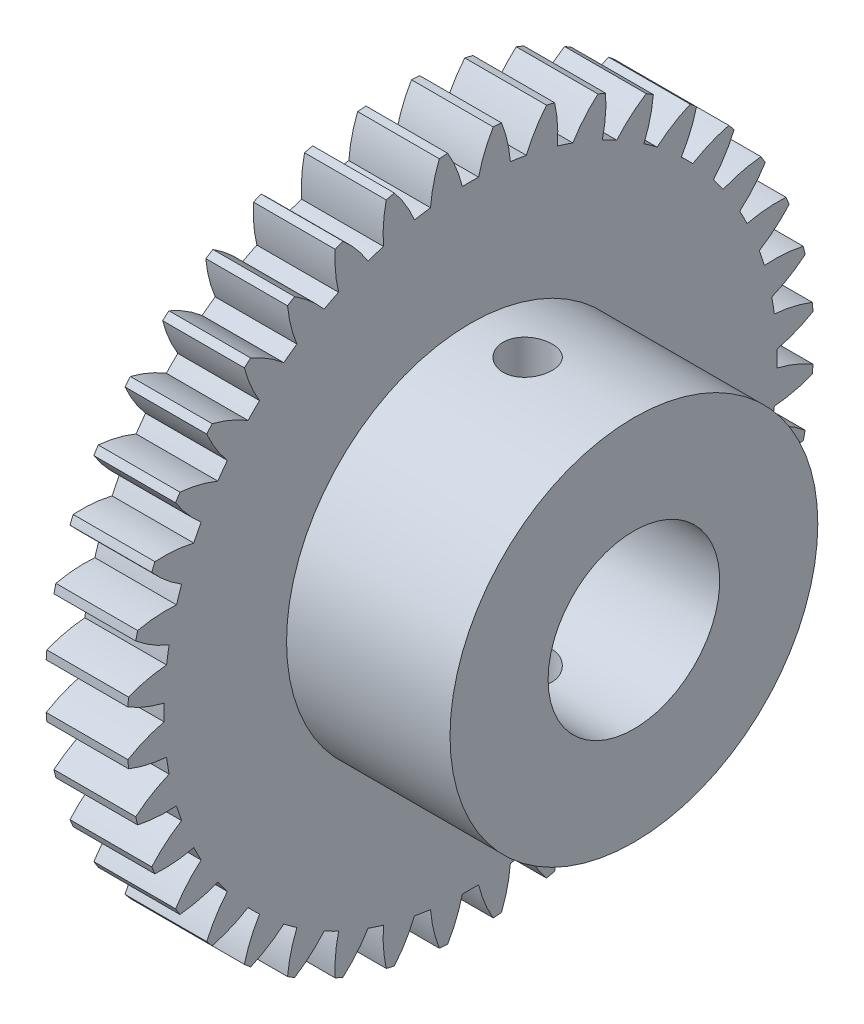
SolidWorks part; units mm, degrees
ref_plane "Plane1" through (0, 0, 0) normal (0, 0, 1) x (1, 0, 0)
ref_plane "Plane2" through (0, 0, 0) normal (0, 1, 0) x (1, 0, 0)
ref_plane "Plane3" through (0, 0, 0) normal (1, 0, 0) x (0, 0, -1)
sketch "HoldingSke" plane through (0, 0, 0) normal (0, 1, 0) x (1, 0, 0)
  line L0 (0, 0) -> (0.766, -0.6428)
  line L1 (-15, 0) -> (100, 0) construction
  line L2 (0, 0) -> (-2.1039, 2.3779)
  line L3 (0, 0) -> (-11.863, 4.5341)
  line L4 (0, 0) -> (6.6156, 5.5511)
  line L5 (0, 0) -> (-46.8476, -17.4728)
  line L6 (0, 0) -> (-4.1448, -2.7965)
  line L7 (-2.1039, 2.3779) -> (8.6586, 51.2059)
  line L8 (-76.2, 54.61) -> (-75.3, 54.61)
  line L9 (-71.009, 38.7566) -> (-53.1078, 45.2721)
  line L10 (-76.2, 71.12) -> (104.1128, 71.12)
  line L11 (0, 0) -> (-5, 0)
  line L12 (-76.2, 101.6) -> (-76.133, 101.6)
  line L13 (24.9733, 27.94) -> (52.9518, 28.4284)
  line L14 (24.9733, 27.94) -> (24.9743, 27.94)
  line L15 (24.9733, 27.94) -> (100.4006, 29.5858)
  line L16 (-63.627, -1) -> (-12.827, -1)
  circle A0 centre (0, 0) radius 5.25
  circle A1 centre (0, 0) radius 18.749
  circle A2 centre (0, 0) radius 37.5
  circle A3 centre (0, 0) radius 5.25
  dimension "MHD" = 37.498
  dimension "Hub_dia" = 75
  dimension "Bore" = 10.5
  dimension "MBD" = 10.5
  dimension "Num_teeth" = 40
  dimension "Pitch" = 1
  dimension "Overall_len" = 50
  dimension "Show_teeth" = 40
  dimension "Thickness" = 5
  dimension "OAL" = 50.0001
  dimension "T_dim" = 0.9
  dimension "Ap" = 20
  dimension "H" = 19.05
  dimension "Pitch_radius" = 180.3128
  dimension "Width" = 5
  dimension "Backlash" = 0.067
  dimension "Addendum_fac" = 1
  dimension "Dedendum_fac" = 1.25
  dimension "Clearance_fac" = 0.25
  dimension "Dedendum_add" = 0.001
  dimension "Module" = 1
sketch "BasProSke" plane through (0, 0, 0) normal (0, 1, 0) x (1, 0, 0)
  line L0 (-10, 0) -> (60, 0) construction
  line L1 (0, 0) -> (0, 21)
  line L2 (0, 0) -> (5, 0)
  line L3 (5, 0) -> (5, 21)
  line L4 (5, 21) -> (0, 21)
  dimension "Thickness" = 5
  dimension "Diameter" = 42
revolve "Base-Revolve" add sketch "BasProSke" angle 360 about L0
sketch "TooCutSke" plane through (0, 0, 0) normal (1, 0, 0) x (0, 0, -1)
  line L1 (0, 0) -> (0, 107) construction
  line L2 (0, 0) -> (-0.9024, 19.9796) construction
  line L3 (0, 0) -> (-3.1366, 39.8544) construction
  line L4 (-0.9024, 19.9796) -> (-1.5683, 19.9272) construction
  arc A0 (0.4963, 18.7424) -> (-0.4963, 18.7424) centre (0, 0) ccw
  arc A1 (1.408, 20.9782) -> (-1.408, 20.9782) centre (0, 0) ccw
  circle A2 centre (0, 0) radius 20 construction
  circle A3 centre (0, 0) radius 18.7939 construction
  arc A4 (-0.4963, 18.7424) -> (-1.408, 20.9782) centre (-8.275, 16.874) ccw
  arc A5 (1.408, 20.9782) -> (0.4963, 18.7424) centre (8.275, 16.874) ccw
  dimension "Root_dia" = 37.498
  dimension "Overcut_dia" = 42.0508
  dimension "Pitch_dia" = 40
  dimension "Base_dia" = 37.5877
  dimension "Flank_rad" = 8
  dimension "Half_ang" = 4.5
  dimension "Half_CT" = 0.6679
extrude "ToothCut" cut sketch "TooCutSke" along normal through all
fillet "Breaks" [suppressed] radius 0.02
fillet "RootFillets" [suppressed] radius 0.251
pattern_circular "TeethCuts" count 40 every 9 about axis through (-10, 0, 0) along (1, 0, 0) of "ToothCut", "RootFillets", "Breaks"
sketch "HubNeaOneSke" plane through (0, 0, 0) normal (-1, 0, 0) x (0, 0, 1)
  circle A0 centre (0, 0) radius 18.749
  dimension "Diameter" = 37.498
extrude "HubNearOne" [suppressed] add sketch "HubNeaOneSke" along normal blind 45.0001
sketch "HubNeaBotSke" plane through (0, 0, 0) normal (-1, 0, 0) x (0, 0, 1)
  circle A0 centre (0, 0) radius 18.749
  dimension "Diameter" = 37.498
extrude "HubNearBoth" [suppressed] add sketch "HubNeaBotSke" along normal blind 22.5
ref_plane "FarPln" through (5, 0, 0) normal (1, 0, 0) x (0, 0, -1)
sketch "HubFarSke" plane through (5, 0, 0) normal (1, 0, 0) x (0, 0, -1)
  circle A0 centre (0, 0) radius 18.749
  dimension "Diameter" = 37.498
extrude "HubFar" [suppressed] add sketch "HubFarSke" along normal blind 22.5
sketch "BorSke" plane through (0, 0, 0) normal (1, 0, 0) x (0, 0, -1)
  circle A0 centre (0, 0) radius 5.25
  dimension "Diameter" = 10.5
extrude "Bore" cut sketch "BorSke" along normal mid plane 100.0001
sketch "KeySke" plane through (0, 0, 0) normal (1, 0, 0) x (0, 0, -1)
  line L0 (-1, 0) -> (-1, 6.15)
  line L1 (-1, 6.15) -> (1, 6.15)
  line L2 (1, 6.15) -> (1, 0)
  line L3 (0, 0) -> (0, 34) construction
  line L4 (-1, 0) -> (1, 0)
  dimension "Offset" = 6.15
  dimension "Width" = 2
extrude "Keyway" [suppressed] cut sketch "KeySke" along normal mid plane 100.0001
pattern_circular "Keyway2" [suppressed] count 2 every 90 about axis through (-10, 0, 0) along (1, 0, 0)
sketch "ｽｹｯﾁ1" plane through (0, 0, 0) normal (-1, 0, 0) x (0, 0, 1)
  circle A0 centre (0, 0) radius 11.25
  circle A1 centre (0, 0) radius 5.25 construction
  circle A2 centre (0, 0) radius 5.25
  dimension "D1" = 6
extrude "ﾎﾞｽ - 押し出し1" add sketch "ｽｹｯﾁ1" against normal blind 15
sketch "ｽｹｯﾁ2" plane through (0, 0, 0) normal (0, 1, 0) x (1, 0, 0)
  line L0 (0, 0) -> (15, 0) construction
  line L1 (15, -11.25) -> (15, 11.25) construction
  circle A0 centre (8.5, 0) radius 1.5
  dimension "D1" = 8.5
  dimension "D2" = 3
extrude "ｶｯﾄ - 押し出し1" cut sketch "ｽｹｯﾁ2" against normal through all both and the other way through all
equation "' \"Module@HoldingSke\" = 6.35"
equation "' \"Num_teeth@HoldingSke\" = 12"
equation "' \"Ap@HoldingSke\" =  20"
equation "' \"Ap@HoldingSke\" = 20"
equation "' \"Width@HoldingSke\" = 0.5 * 25.4"
equation "' \"Hub_dia@HoldingSke\"= 1 * 25.4"
equation "' \"Hub_dia@HoldingSke\" = 1 * 25.4"
equation "' \"Overall_len@HoldingSke\" = 1.0 * 25.4"
equation "' \"Bore@HoldingSke\" = 0.75 * 25.4"
equation "' \"T_dim@HoldingSke\" = 0.1 * 25.4"
equation "' \"Width@KeySke\" = 0.25 * 25.4"
equation "' \"Show_teeth@HoldingSke\" = 13"
equation "' \"Backlash@HoldingSke\" = 0.009 * 25.4"
equation "' \"Addendum_fac@HoldingSke\" = 1.0"
equation "' \"Dedendum_fac@HoldingSke\" = 1.25"
equation "' \"Dedendum_add@HoldingSke\" = 0.00005 * 25.4"
equation "' \"Clearance_fac@HoldingSke\" = 0.25"
equation "\"Pitch@HoldingSke\" = 1 / \"Module@HoldingSke\""
equation "\"Overcut_dia@TooCutSke\" = (\"Num_teeth@HoldingSke\" + 2 * \"Addendum_fac@HoldingSke\") / \"Pitch@HoldingSke\" + 0.002 * 25.4"
equation "\"Pitch_dia@TooCutSke\" = \"Num_teeth@HoldingSke\" / \"Pitch@HoldingSke\""
equation "\"Base_dia@TooCutSke\" = \"Num_teeth@HoldingSke\" / \"Pitch@HoldingSke\" * cos((\"Ap@HoldingSke\"  * 3.14159265 / 180))"
equation "\"Root_dia@TooCutSke\" = (\"Num_teeth@HoldingSke\" + 2) / \"Pitch@HoldingSke\" - 2 * (\"Addendum_fac@HoldingSke\" + \"Dedendum_fac@HoldingSke\") / \"Pitch@HoldingSke\" - \"Dedendum_add@HoldingSke\" * 2"
equation "\"Half_ang@TooCutSke\" = 180 / \"Num_teeth@HoldingSke\""
equation "\"Half_CT@TooCutSke\" = \"Num_teeth@HoldingSke\" / \"Pitch@HoldingSke\" * sin((3.14159265 / 2 / \"Num_teeth@HoldingSke\")) / 2 - 7 * \"Backlash@HoldingSke\" / 4"
equation "\"Flank_rad@TooCutSke\" = \"Num_teeth@HoldingSke\" / \"Pitch@HoldingSke\" / 5"
equation "\"Radius@RootFillets\" = \"Clearance_fac@HoldingSke\" / \"Pitch@HoldingSke\" + \"Dedendum_add@HoldingSke\""
equation "\"Break_rad@Breaks\" = 0.02 / \"Pitch@HoldingSke\""
equation "\"Thickness@HoldingSke\" = \"Width@HoldingSke\""
equation "\"OAL@HoldingSke\" = \"Thickness@HoldingSke\""
equation "\"MHD@HoldingSke\" = (\"Num_teeth@HoldingSke\" + 2) / \"Pitch@HoldingSke\" - 2 * (\"Addendum_fac@HoldingSke\" + \"Dedendum_fac@HoldingSke\")  / \"Pitch@HoldingSke\" - \"Dedendum_add@HoldingSke\" * 2"
equation "\"MBD@HoldingSke\" = (\"Num_teeth@HoldingSke\" + 2) / \"Pitch@HoldingSke\" - 2 * (\"Addendum_fac@HoldingSke\" + \"Dedendum_fac@HoldingSke\")  / \"Pitch@HoldingSke\" - \"Dedendum_add@HoldingSke\" * 2 - 0.002 * 25.4"
equation "\"MHD@HoldingSke\" = ((sgn( \"MHD@HoldingSke\" - \"Hub_dia@HoldingSke\" )-1)*( \"MHD@HoldingSke\" - \"Hub_dia@HoldingSke\" ))/-2+ \"Hub_dia@HoldingSke\""
equation "\"MBD@HoldingSke\" = ((sgn( \"MBD@HoldingSke\" - \"Bore@HoldingSke\" )-1)*( \"MBD@HoldingSke\" - \"Bore@HoldingSke\" ))/-2+ \"Bore@HoldingSke\""
equation "\"OAL@HoldingSke\" = ((sgn( \"OAL@HoldingSke\" - \"Overall_len@HoldingSke\" )+1)*( \"OAL@HoldingSke\" - \"Overall_len@HoldingSke\" ))/2 + \"Overall_len@HoldingSke\" + 0.000002 * 25.4"
equation "\"Num_teeth@TeethCuts\" = int( \"Show_teeth@HoldingSke\" ) + 1"
equation "\"Num_teeth@TeethCuts\" = ((sgn( \"Num_teeth@TeethCuts\" - \"Num_teeth@HoldingSke\" )-1)*( \"Num_teeth@TeethCuts\" - \"Num_teeth@HoldingSke\" ))/-2+ \"Num_teeth@HoldingSke\""
equation "\"Num_teeth@TeethCuts\" = ((sgn( \"Num_teeth@TeethCuts\" - 2.0)+1)*( \"Num_teeth@TeethCuts\" - 2.0))/2 +2.0"
equation "\"Angle@TeethCuts\" = 360.0 / \"Num_teeth@HoldingSke\""
equation "\"Diameter@BasProSke\" = (\"Num_teeth@HoldingSke\" + 2 * \"Addendum_fac@HoldingSke\") / \"Pitch@HoldingSke\""
equation "\"Thickness@BasProSke\"  = \"Thickness@HoldingSke\""
equation "' \"Fillet_rad@BasProSke\" =  \"Thickness@HoldingSke\" * 0.05"
equation "' \"Fillet_rad@BasProSke\" = \"Thickness@HoldingSke\" * 0.05"
equation "\"MHD@HoldingSke\" = ((sgn( \"MHD@HoldingSke\" - \"Root_dia@TooCutSke\" )-1)*( \"MHD@HoldingSke\" - \"Root_dia@TooCutSke\" ))/-2+ \"Root_dia@TooCutSke\""
equation "\"Diameter@HubNeaOneSke\" = \"MHD@HoldingSke\""
equation "\"Length@HubNearOne\" = \"OAL@HoldingSke\" - \"Thickness@BasProSke\""
equation "\"Diameter@HubNeaBotSke\" = \"MHD@HoldingSke\""
equation "\"Length@HubNearBoth\" = ( \"OAL@HoldingSke\" - \"Thickness@BasProSke\" ) / 2.0"
equation "\"Thickness@FarPln\" = \"Thickness@BasProSke\""
equation "\"Diameter@HubFarSke\" = \"MHD@HoldingSke\""
equation "\"Length@HubFar\" = ( \"OAL@HoldingSke\" - \"Thickness@BasProSke\" ) / 2.0"
equation "\"Diameter@BorSke\" = \"MBD@HoldingSke\""
equation "\"D1@Bore\" = \"OAL@HoldingSke\" * 2.0"
equation "\"D1@Keyway\" = \"OAL@HoldingSke\" * 2.0"
equation "\"Offset@KeySke\" = \"T_dim@HoldingSke\" + \"MBD@HoldingSke\" / 2.0"
